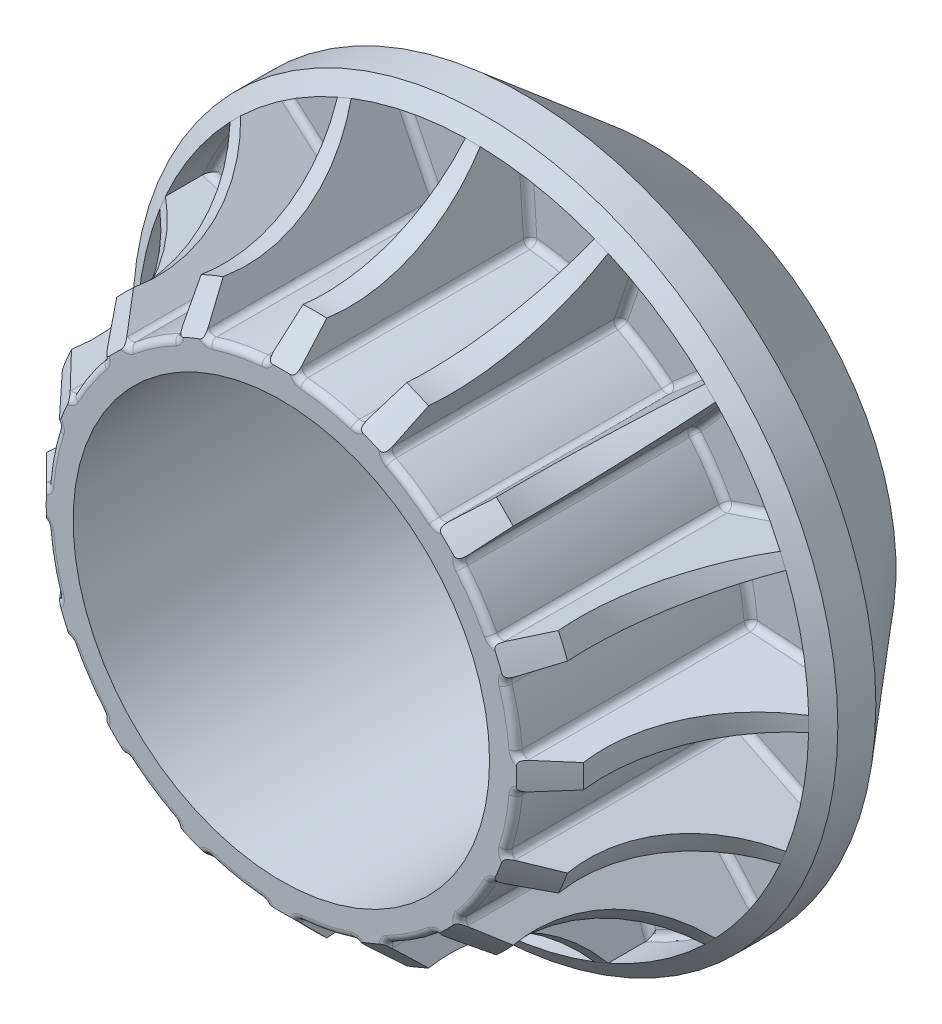
SolidWorks part; units mm, degrees
material "7075-T6 (SN)"
ref_plane "Front Plane" through (0, 0, 0) normal (0, 0, 1) x (1, 0, 0)
ref_plane "Top Plane" through (0, 0, 0) normal (0, 1, 0) x (1, 0, 0)
ref_plane "Right Plane" through (0, 0, 0) normal (1, 0, 0) x (0, 0, -1)
sketch "Sketch1" plane through (0, 0, 0) normal (0, 0, 1) x (1, 0, 0)
  circle A0 centre (0, 0) radius 35
  circle A1 centre (0, 0) radius 31
  dimension "D1" = 62
  dimension "D2" = 70
extrude "Boss-Extrude1" add sketch "Sketch1" against normal blind 55
sketch "Sketch2" plane through (0, 0, 0) normal (1, 0, 0) x (0, 0, -1)
  line L0 (55, 35) -> (35, 35)
  line L1 (55, 35) -> (0, 35) construction
  line L2 (35, 35) -> (35, 50)
  line L3 (35, 50) -> (28.5, 50)
  line L4 (28.5, 50) -> (28.5, 52.5)
  line L5 (28.5, 52.5) -> (36, 52.5)
  line L6 (36, 52.5) -> (55, 36.5)
  line L7 (55, 36.5) -> (55, 35)
  dimension "D1" = 20
  dimension "D2" = 6.5
  dimension "D3" = 7.5
  dimension "D4" = 36.5
  dimension "D5" = 50
  dimension "D6" = 52.5
revolve "Revolve1" add sketch "Sketch2" angle 360 about axis through (0, 0, -55) along (0, 0, 1)
sketch "Sketch3" plane through (0, 0, 0) normal (0, 0, 1) x (1, 0, 0)
  line L0 (-1.1, 49.9879) -> (-2.1, 34.9369)
  line L1 (1.1, 49.9879) -> (2.1, 34.9369)
  arc A0 (-2.1, 34.9369) -> (2.1, 34.9369) centre (0, 0) cw
  circle A1 centre (0, 0) radius 35 construction
  arc A2 (-1.1, 49.9879) -> (1.1, 49.9879) centre (0, 0) cw
  circle A3 centre (0, 0) radius 50 construction
  circle A4 centre (0, 0) radius 50 construction
  point P8 (0, 35)
  point P11 (0, 50)
  dimension "D1" = 2.2
  dimension "D2" = 4.2
extrude "Boss-Extrude2" add sketch "Sketch3" against normal up to surface (35 mm away) up to face at (35, 0, -35)
pattern_circular "CirPattern1" count 16 over 360 about axis through (0, 0, 0) along (0, 0, 1) of "Boss-Extrude2"
fillet "Fillet1" radius 1 144 edges at (-38.6179, -17.7279, -35) (-39.8425, -14.7715, -35) (-19.445, -29.1014, 0) (-41.5735, -27.7785, -35) (-29.1014, -19.445, -35) (-26.1891, -23.2192, -17.5) (-23.2192, -26.1891, -17.5) (-31.1568, -28.8941, 0) (-28.8941, -31.1568, 0) (-28.8941, -31.1568, -35) (-31.1568, -28.8941, -35) (-6.8282, -34.3275, 0) (-27.7785, -41.5735, -35) (-19.445, -29.1014, -35) (-15.3099, -31.4739, -17.5) (-11.4296, -33.0812, -17.5) (-17.7279, -38.6179, 0) (-14.7715, -39.8425, 0) (-14.7715, -39.8425, -35) (-17.7279, -38.6179, -35) (6.8282, -34.3275, 0) (-9.7545, -49.0393, -35) (-6.8282, -34.3275, -35) (-2.1, -34.9369, -17.5) (2.1, -34.9369, -17.5) (-1.6, -42.4624, 0) (1.6, -42.4624, 0) (1.6, -42.4624, -35) (-1.6, -42.4624, -35) (19.445, -29.1014, 0) (9.7545, -49.0393, -35) (6.8282, -34.3275, -35) (11.4296, -33.0812, -17.5) (15.3099, -31.4739, -17.5) (14.7715, -39.8425, 0) (17.7279, -38.6179, 0) (17.7279, -38.6179, -35) (14.7715, -39.8425, -35) (29.1014, -19.445, 0) (27.7785, -41.5735, -35) (19.445, -29.1014, -35) (23.2192, -26.1891, -17.5) (26.1891, -23.2192, -17.5) (28.8941, -31.1568, 0) (31.1568, -28.8941, 0) (31.1568, -28.8941, -35) (28.8941, -31.1568, -35) (34.3275, -6.8282, 0) (41.5735, -27.7785, -35) (9.7545, 49.0393, -35) (29.1014, -19.445, -35) (31.4739, -15.3099, -17.5) (33.0812, -11.4296, -17.5) (38.6179, -17.7279, 0) (39.8425, -14.7715, 0) (39.8425, -14.7715, -35) (38.6179, -17.7279, -35) (6.8282, 34.3275, -35) (34.3275, 6.8282, 0) (49.0393, -9.7545, -35) (34.3275, -6.8282, -35) (34.9369, -2.1, -17.5) (34.9369, 2.1, -17.5) (42.4624, -1.6, 0) (42.4624, 1.6, 0) (42.4624, 1.6, -35) (42.4624, -1.6, -35) (-6.8282, 34.3275, 0) (29.1014, 19.445, 0) (49.0393, 9.7545, -35) (34.3275, 6.8282, -35) (33.0812, 11.4296, -17.5) (31.4739, 15.3099, -17.5) (39.8425, 14.7715, 0) (2.1, 34.9369, -17.5) (38.6179, 17.7279, 0) (38.6179, 17.7279, -35) (39.8425, 14.7715, -35) (-2.1, 34.9369, -17.5) (19.445, 29.1014, 0) (1.6, 42.4624, 0) (41.5735, 27.7785, -35) (29.1014, 19.445, -35) (26.1891, 23.2192, -17.5) (23.2192, 26.1891, -17.5) (31.1568, 28.8941, 0) (28.8941, 31.1568, 0) (-1.6, 42.4624, 0) (28.8941, 31.1568, -35) (31.1568, 28.8941, -35) (-1.6, 42.4624, -35) (1.6, 42.4624, -35) (6.8282, 34.3275, 0) (27.7785, 41.5735, -35) (19.445, 29.1014, -35) (15.3099, 31.4739, -17.5) (11.4296, 33.0812, -17.5) (17.7279, 38.6179, 0) (14.7715, 39.8425, 0) (14.7715, 39.8425, -35) (17.7279, 38.6179, -35) (-9.7545, 49.0393, -35) (-6.8282, 34.3275, -35) (-19.445, 29.1014, 0) (-11.4296, 33.0812, -17.5) (-15.3099, 31.4739, -17.5) (-14.7715, 39.8425, 0) (-17.7279, 38.6179, 0) (-17.7279, 38.6179, -35) (-14.7715, 39.8425, -35) (-29.1014, 19.445, 0) (-27.7785, 41.5735, -35) (-19.445, 29.1014, -35) (-23.2192, 26.1891, -17.5) (-26.1891, 23.2192, -17.5) (-28.8941, 31.1568, 0) (-31.1568, 28.8941, 0) (-31.1568, 28.8941, -35) (-28.8941, 31.1568, -35) (-34.3275, 6.8282, 0) (-41.5735, 27.7785, -35) (-29.1014, 19.445, -35) (-31.4739, 15.3099, -17.5) (-33.0812, 11.4296, -17.5) (-38.6179, 17.7279, 0) (-39.8425, 14.7715, 0) (-39.8425, 14.7715, -35) (-38.6179, 17.7279, -35) (-34.3275, -6.8282, 0) (-49.0393, 9.7545, -35) (-34.3275, 6.8282, -35) (-34.9369, 2.1, -17.5) (-34.9369, -2.1, -17.5) (-42.4624, 1.6, 0) (-42.4624, -1.6, 0) (-42.4624, -1.6, -35) (-42.4624, 1.6, -35) (-29.1014, -19.445, 0) (-49.0393, -9.7545, -35) (-34.3275, -6.8282, -35) (-33.0812, -11.4296, -17.5) (-31.4739, -15.3099, -17.5) (-39.8425, -14.7715, 0) (-38.6179, -17.7279, 0)
sketch "Sketch4" plane through (0, 0, 0) normal (1, 0, 0) x (0, 0, -1)
  line L0 (0, 35) -> (8.067, 35) construction
  line L1 (34, 0) -> (1, 0) construction
  line L2 (0, 24.5326) -> (0, 35.2867) construction
  line L3 (0, 35) -> (5, 40)
  line L4 (28.5, 49.9879) -> (32.5071, 55.45)
  line L6 (32.5071, 55.45) -> (0, 55.45)
  line L7 (0, 55.45) -> (0, 35)
  arc A0 (5, 40) -> (28.5, 49.9879) centre (8.3425, 64.7755) ccw
  dimension "D4" = 25
  dimension "D1" = 35
  dimension "D2" = 45
  dimension "D3" = 5
revolve "Cut-Revolve1" cut sketch "Sketch4" angle 360 about axis through (0, 0, -55) along (0, 0, 1)
